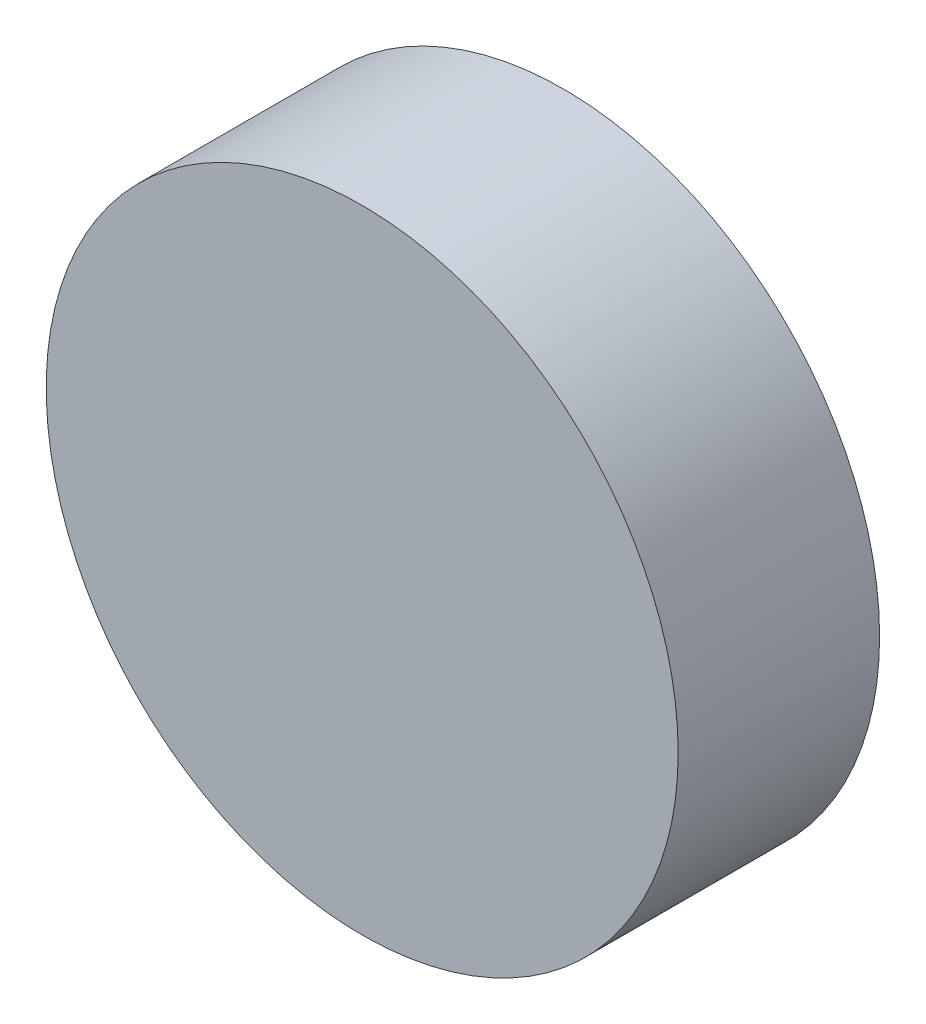
SolidWorks part; units mm, degrees
ref_plane "Front Plane" through (0, 0, 0) normal (0, 0, 1) x (1, 0, 0)
ref_plane "Top Plane" through (0, 0, 0) normal (0, 1, 0) x (1, 0, 0)
ref_plane "Right Plane" through (0, 0, 0) normal (1, 0, 0) x (0, 0, -1)
sketch "Sketch1" plane through (0, 0, 0) normal (0, 0, 1) x (1, 0, 0)
  circle A0 centre (0, 0) radius 40
  dimension "D1" = 80
extrude "Boss-Extrude1" add sketch "Sketch1" along normal blind 25.5
sketch "Sketch2" plane through (0, 0, 0) normal (0, 0, -1) x (-1, 0, 0)
  line L0 (0, 40) -> (0, -40) construction
  line L1 (-40, 0) -> (40, 0) construction
  circle A0 centre (0, 0) radius 40 construction
  circle A1 centre (0, 33.65) radius 3.45
  circle A2 centre (33.65, 0) radius 3.45
  circle A3 centre (0, -33.65) radius 3.45
  circle A4 centre (-33.65, 0) radius 3.45
  dimension "D1" = 6.9
  dimension "D2" = 2.9
  dimension "D3" = 2.9
extrude "Cut-Extrude1" cut sketch "Sketch2" against normal blind 5
